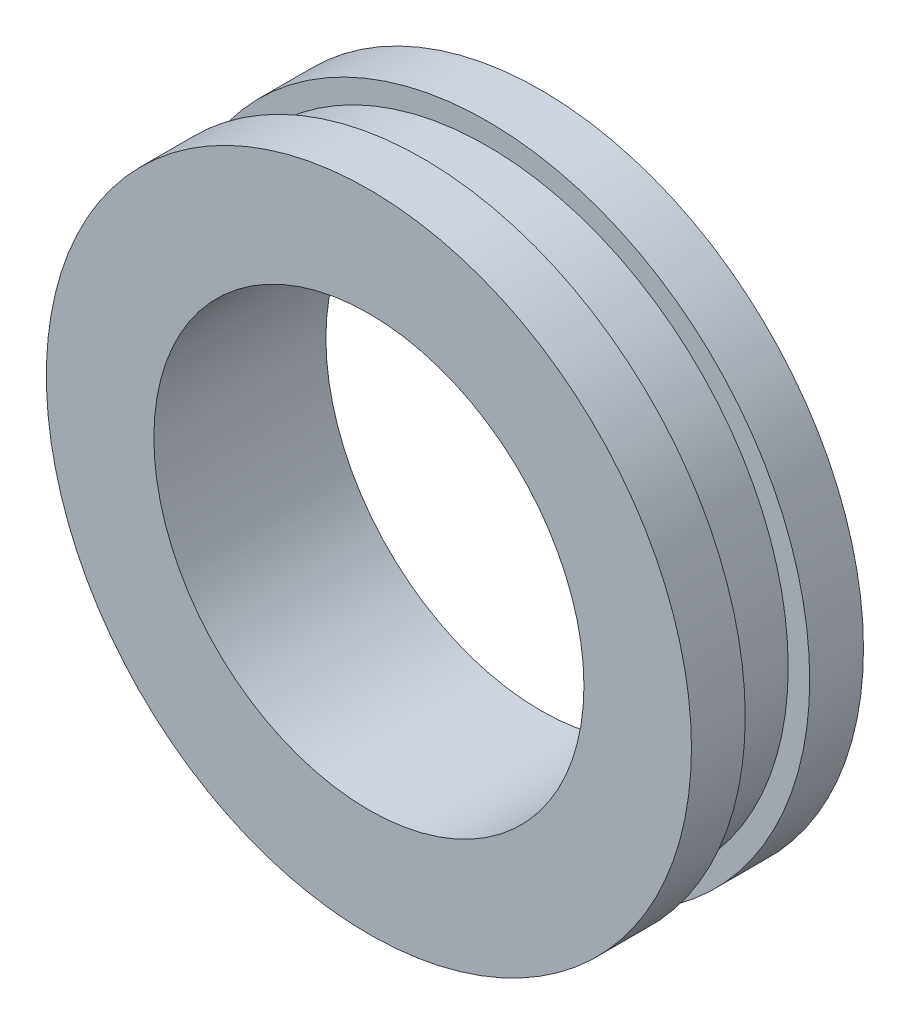
SolidWorks part; units mm, degrees
material "AISI 1020"
ref_plane "Alzado" through (0, 0, 0) normal (0, 0, 1) x (1, 0, 0)
ref_plane "Planta" through (0, 0, 0) normal (0, 1, 0) x (1, 0, 0)
ref_plane "Vista lateral" through (0, 0, 0) normal (1, 0, 0) x (0, 0, -1)
sketch "Croquis1" plane through (0, 0, 0) normal (1, 0, 0) x (0, 0, -1)
  line L0 (-17.6913, 0) -> (16.9345, 0) construction
  line L1 (-2, 5) -> (2, 5)
  line L2 (2, 5) -> (2, 7.5)
  line L3 (2, 7.5) -> (0.75, 7.5)
  line L4 (0.75, 7.5) -> (0.75, 7)
  line L5 (0.75, 7) -> (-0.75, 7)
  line L6 (-0.75, 7) -> (-0.75, 7.5)
  line L7 (-0.75, 7.5) -> (-2, 7.5)
  line L8 (-2, 7.5) -> (-2, 5)
  point P10 (0, 7)
  point P12 (0, 5)
  point P16 (-1.375, 7.5)
  dimension "D1" = 10
  dimension "D2" = 4
  dimension "D3" = 1.25
  dimension "D4" = 15
  dimension "D5" = 0.5
revolve "Revolución1" add sketch "Croquis1" angle 360 about L0
